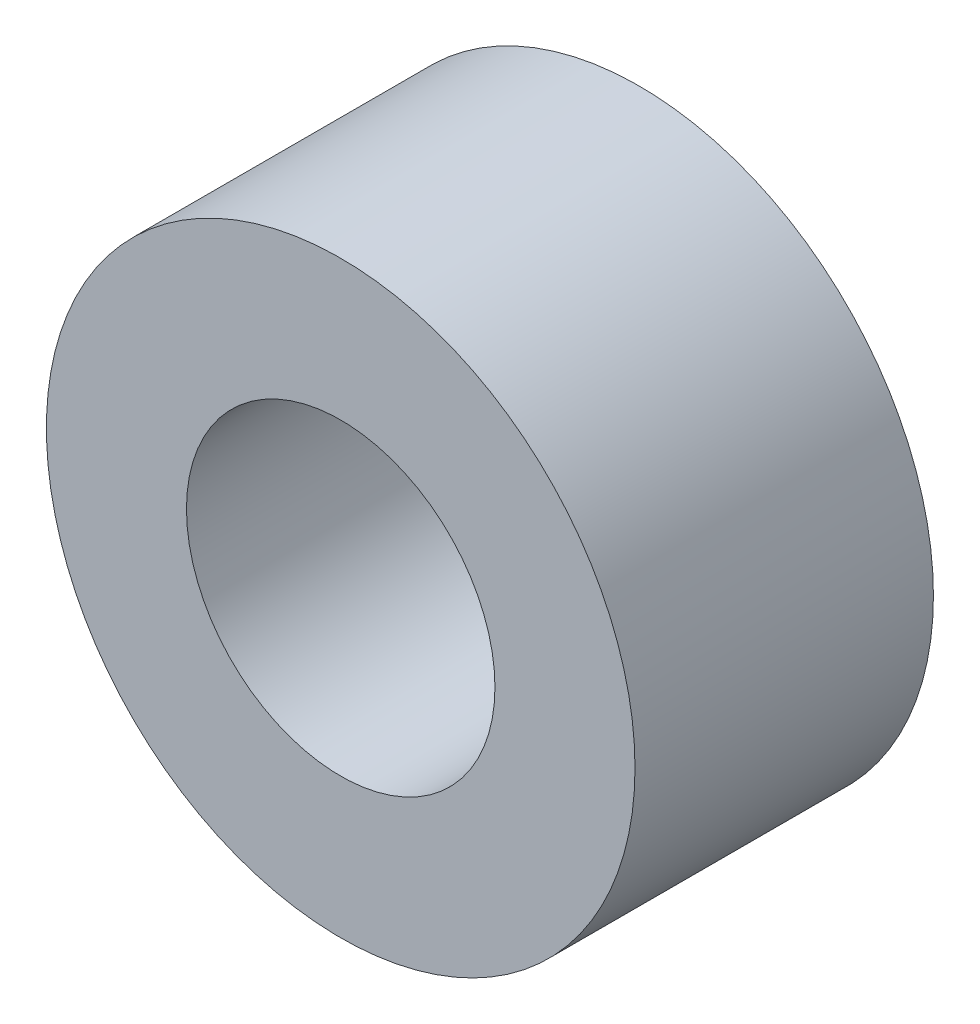
SolidWorks part; units mm, degrees
ref_plane "Plan de face" through (0, 0, 0) normal (1, 0, 0) x (0, 1, 0)
ref_plane "Plan de dessus" through (0, 0, 0) normal (0, 0, 1) x (0, 1, 0)
ref_plane "Plan de droite" through (0, 0, 0) normal (0, 1, 0) x (-1, 0, 0)
sketch "Esquisse1" plane through (0, 0, 0) normal (0, 0, 1) x (0, 1, 0)
  circle A0 centre (0, 0) radius 7.89
  circle A1 centre (0, 0) radius 4.135
  dimension "D1" = 8.27
  dimension "D2" = 15.78
extrude "Boss.-Extru.1" add sketch "Esquisse1" along normal blind 8
